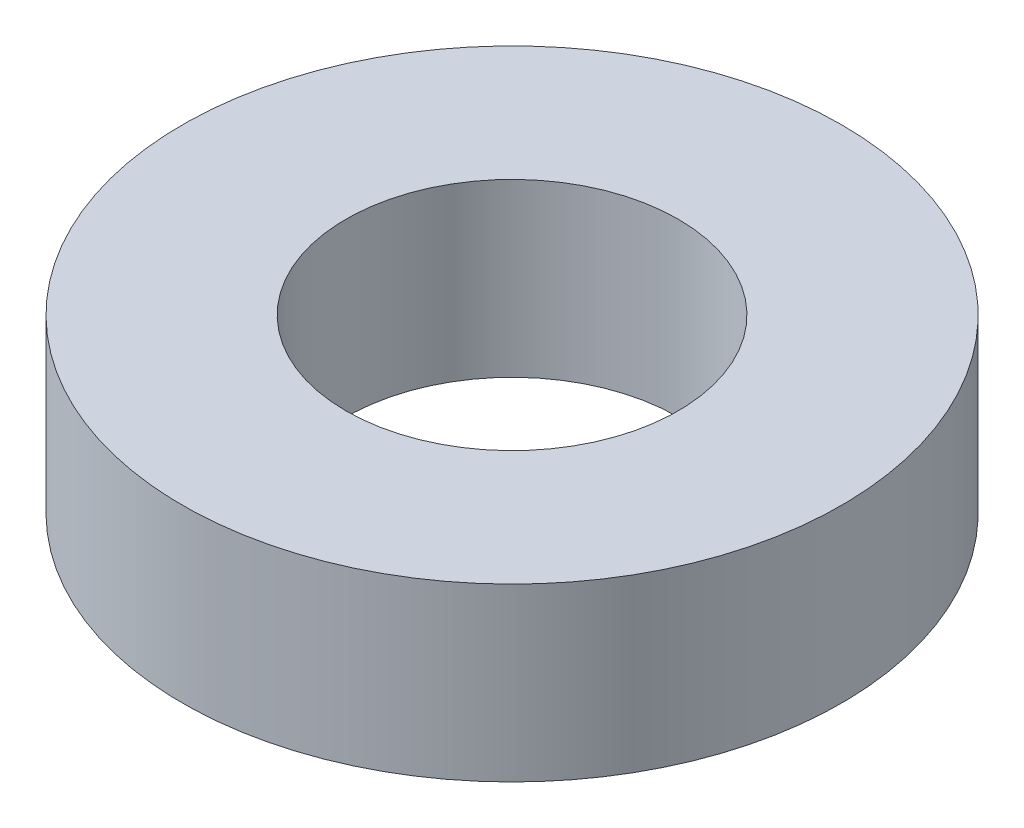
SolidWorks part; units mm, degrees
material "1060 Alloy"
ref_plane "Front Plane" through (0, 0, 0) normal (0, 0, 1) x (1, 0, 0)
ref_plane "Top Plane" through (0, 0, 0) normal (0, 1, 0) x (1, 0, 0)
ref_plane "Right Plane" through (0, 0, 0) normal (1, 0, 0) x (0, 0, -1)
sketch "Sketch1" plane through (0, 0, 0) normal (0, 1, 0) x (1, 0, 0)
  circle A0 centre (0, 0) radius 3.2004
  circle A1 centre (0, 0) radius 6.35
  dimension "D1" = 12.7
  dimension "D2" = 6.4008
extrude "Boss-Extrude1" add sketch "Sketch1" along normal blind 3.302
